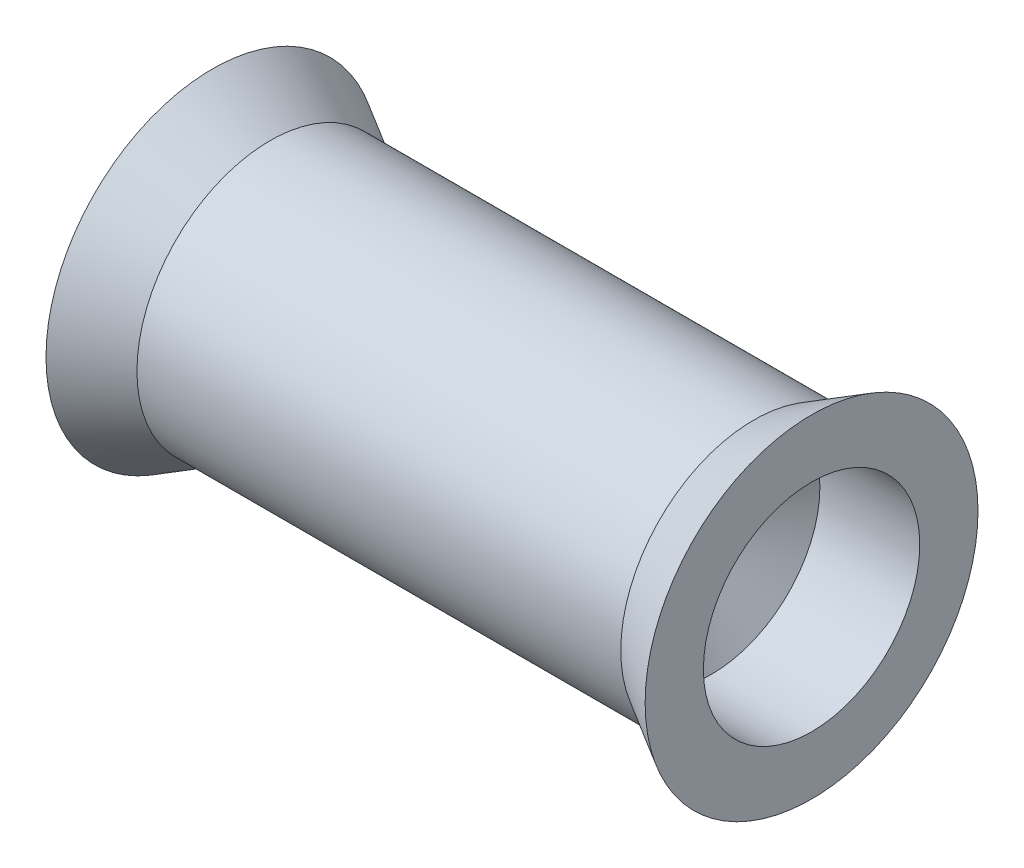
SolidWorks part; units mm, degrees
revolve "Cut-to-GripLength" cut sketch "Sketch2" angle 360 about L0
sketch "Sketch2" plane through (0, 0, 0) normal (0, 0, 1) x (1, 0, 0)
  line L0 (-30, 0) -> (30, 0) construction
  line L1 (-30, 0) -> (31, 0) construction
  line L3 (-11, 0) -> (-9, 0)
  line L4 (-11, 0) -> (-11, 5)
  line L5 (-11, 5) -> (-9, 5)
  line L6 (-9, 0) -> (-9, 5)
  line L7 (9, 0) -> (11, 0)
  line L8 (9, 0) -> (9, 5)
  line L9 (9, 5) -> (11, 5)
  line L10 (11, 0) -> (11, 5)
  dimension "GripLength" = 18
  dimension "D1" = 9
  dimension "D2" = 22
  dimension "D3" = 11
  dimension "D4" = 10
revolve "Base-Revolve" add sketch "Sketch1" angle 360 about L0
sketch "Sketch1" plane through (0, 0, 0) normal (0, 0, 1) x (1, 0, 0)
  line L0 (-30, 0) -> (31, 0) construction
  line L2 (-10, 0) -> (10, 0)
  line L3 (-10, 0) -> (-10, 4)
  line L4 (-10, 4) -> (10, 4)
  line L5 (10, 0) -> (10, 4)
  dimension "Length" = 20
  dimension "Diameter" = 8
material "Plain Carbon Steel"
ref_plane "Plane1" through (0, 0, 0) normal (0, 0, 1) x (1, 0, 0)
ref_plane "Plane2" through (0, 0, 0) normal (0, 1, 0) x (1, 0, 0)
ref_plane "Plane3" through (0, 0, 0) normal (1, 0, 0) x (0, 0, -1)
other "Configuration Table"
sketch "Sketch3" plane through (0, 0, 0) normal (0, 0, 1) x (1, 0, 0)
  line L0 (-23, 0) -> (23, 0) construction
  line L1 (-30, 0) -> (31, 0) construction
  line L2 (-10.5, 4) -> (-10.5, 0)
  line L3 (-10.5, 0) -> (-9, 0)
  line L4 (-10.5, 4) -> (-9, 5)
  line L5 (-9, 5) -> (-9, 0)
  line L6 (10.5, 4) -> (9, 5)
  line L7 (9, 5) -> (9, 0)
  line L10 (10.5, 4) -> (10.5, 0)
  line L11 (10.5, 0) -> (9, 0)
  line L12 (-9, 4) -> (-9, -4) construction
  line L13 (9, -4) -> (9, 4) construction
  dimension "D1" = 8
  dimension "D2" = 10
  dimension "D3" = 1.5
revolve "HeadTypeA" [suppressed] add sketch "Sketch3" angle 360 about L0
sketch "Sketch4" plane through (0, 0, 0) normal (0, 0, 1) x (1, 0, 0)
  line L0 (-20, 0) -> (20, 0) construction
  line L1 (-30, 0) -> (31, 0) construction
  line L2 (-9, 0) -> (-9, 5)
  line L3 (-9, 5) -> (-7.2679, 4)
  line L4 (-7.2679, 0) -> (-9, 0)
  line L5 (-9, -5) -> (-7.2679, -4) construction
  line L6 (0, 0) -> (0, 14) construction
  line L7 (7.2679, 0) -> (9, 0)
  line L8 (9, 0) -> (9, 5)
  line L9 (-7.2679, 4) -> (-7.2679, 0)
  line L10 (7.2679, 4) -> (7.2679, 0)
  line L11 (9, 5) -> (7.2679, 4)
  dimension "D1" = 8
  dimension "D2" = 10
  dimension "D3" = 60
  dimension "D4" = 18
revolve "HeadTypeB" add sketch "Sketch4" angle 360 about L0
sketch "Sketch5" plane through (0, 0, 0) normal (0, 0, 1) x (1, 0, 0)
  line L0 (-22, 0) -> (21, 0) construction
  line L1 (-30, 0) -> (31, 0) construction
  line L2 (-4.1236, 0) -> (-6, 3.25)
  line L4 (-6, 3.25) -> (-10, 3.25)
  line L5 (-10, 3.25) -> (-10, 0)
  line L6 (-10, 0) -> (-4.1236, 0)
  line L7 (4.1236, 0) -> (6, 3.25)
  line L8 (6, 3.25) -> (10, 3.25)
  line L9 (10, 3.25) -> (10, 0)
  line L10 (10, 0) -> (4.1236, 0)
  line L11 (-4.1236, 0) -> (-6, -3.25) construction
  line L12 (4.1236, 0) -> (6, -3.25) construction
  dimension "D2" = 10
  dimension "D1" = 20
  dimension "HoleDepth" = 4
  dimension "D3" = 4
  dimension "D4" = 120
  dimension "D5" = 120
  dimension "HoleDia" = 6.5
  dimension "D6" = 6.5
revolve "HoleTypeA" cut sketch "Sketch5" angle 360 about L0
sketch "Sketch6" plane through (0, 0, 0) normal (0, 0, 1) x (1, 0, 0)
  line L0 (-22, 0) -> (22, 0) construction
  line L1 (-30, 0) -> (31, 0) construction
  line L2 (-10, 4) -> (-7.6906, 0)
  line L4 (-7.6906, 0) -> (-10, 0)
  line L5 (-10, 0) -> (-10, 4)
  line L6 (-10, -4) -> (-7.6906, 0) construction
  line L7 (10, -4) -> (7.6906, 0) construction
  line L8 (7.6906, 0) -> (10, 0)
  line L9 (10, 0) -> (10, 4)
  line L10 (10, 4) -> (7.6906, 0)
  dimension "D1" = 120
  dimension "D2" = 8
  dimension "D3" = 120
  dimension "D4" = 20
  dimension "D5" = 10
revolve "HoleTypeB" [suppressed] cut sketch "Sketch6" angle 360 about L0
equation "\"D1@Sketch2\" = \"GripLength@Sketch2\" / 2"
equation "\"D2@Sketch2\" = \"Length@Sketch1\" + 2"
equation "\"D3@Sketch2\" = \"D2@Sketch2\" / 2"
equation "\"D4@Sketch2\" = \"Diameter@Sketch1\" + 2"
equation "\"D1@Sketch3\" = \"Diameter@Sketch1\""
equation "\"D2@Sketch3\" = \"Diameter@Sketch1\" * 1.25"
equation "\"D3@Sketch3\" = \"HeadHt@Sketch3\""
equation "\"D1@Sketch5\" = \"Length@Sketch1\""
equation "\"D2@Sketch5\" = \"D1@Sketch5\" / 2"
equation "\"D3@Sketch5\" = \"HoleDepth@Sketch5\""
equation "\"D5@Sketch5\" = \"D4@Sketch5\""
equation "\"D6@Sketch5\" = \"HoleDia@Sketch5\""
equation "\"D2@Sketch6\" = \"Diameter@Sketch1\""
equation "\"D3@Sketch6\" = \"D1@Sketch6\""
equation "\"D4@Sketch6\" = \"Length@Sketch1\""
equation "\"D5@Sketch6\" = \"D4@Sketch6\" / 2"
equation "\"D1@Sketch4\" = \"Diameter@Sketch1\""
equation "\"D2@Sketch4\" = \"Diameter@Sketch1\" * 1.25"
equation "\"D4@Sketch4\" = \"GripLength@Sketch2\""
